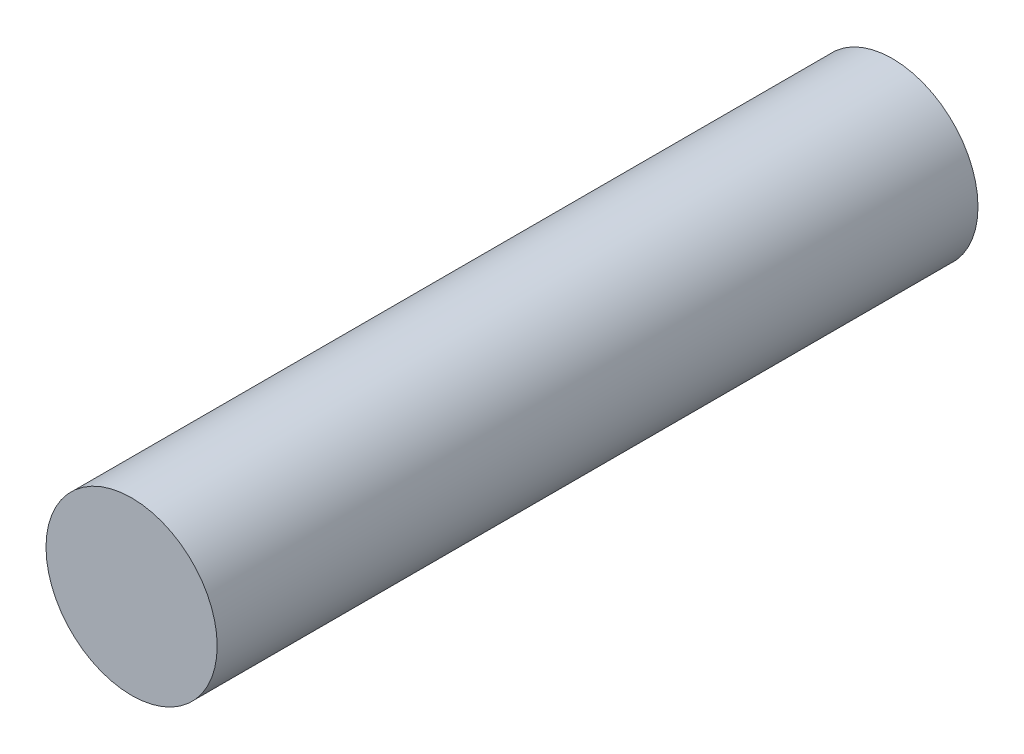
SolidWorks part; units mm, degrees
ref_plane "Front Plane" through (0, 0, 0) normal (0, 0, 1) x (1, 0, 0)
ref_plane "Top Plane" through (0, 0, 0) normal (0, 1, 0) x (1, 0, 0)
ref_plane "Right Plane" through (0, 0, 0) normal (1, 0, 0) x (0, 0, -1)
sketch "Sketch1" plane through (0, 0, 0) normal (0, 0, 1) x (1, 0, 0)
  circle A0 centre (0, 0) radius 9
  dimension "D1" = 18
extrude "Boss-Extrude1" add sketch "Sketch1" along normal mid plane 80
